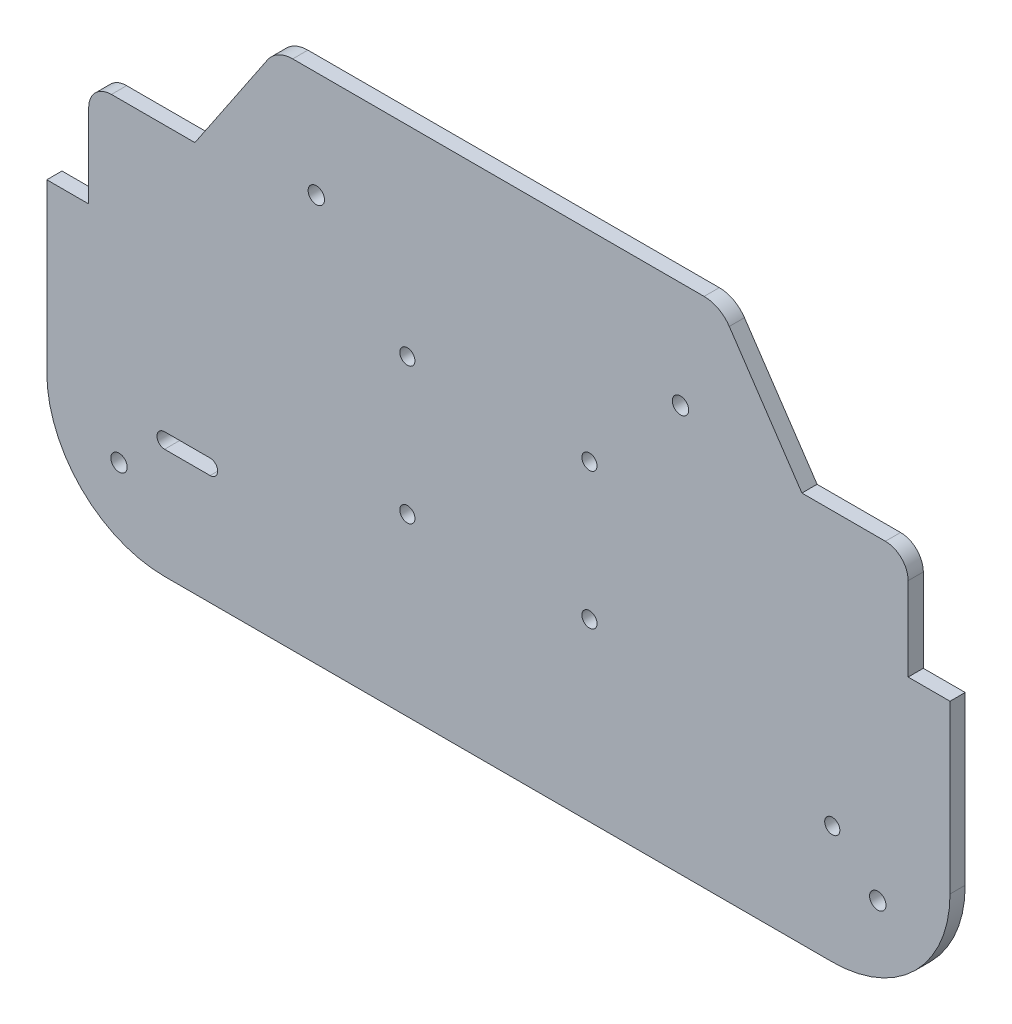
SolidWorks part; units mm, degrees
material "S-Glass Fiber"
ref_plane "Front Plane" through (0, 0, 0) normal (0, 0, 1) x (1, 0, 0)
ref_plane "Top Plane" through (0, 0, 0) normal (0, 1, 0) x (1, 0, 0)
ref_plane "Right Plane" through (0, 0, 0) normal (1, 0, 0) x (0, 0, -1)
ref_plane "Plane1" through (0, 0, -196.85) normal (0, 0, 1) x (1, 0, 0)
sketch "Sketch1" plane through (0, 0, -196.85) normal (0, 0, 1) x (1, 0, 0)
  line L0 (46.4188, -88.9) -> (21.7892, -88.9)
  line L1 (18.1971, -80.2279) -> (61.1779, -37.2471)
  line L2 (69.85, -40.8392) -> (69.85, -65.4688)
  line L3 (-3.5921, -81.3625) -> (-50.8825, -34.0721)
  line L4 (-47.2904, -25.4) -> (47.2904, -25.4)
  line L5 (50.8825, -34.0721) -> (3.5921, -81.3625)
  line L6 (-94.488, -136.525) -> (-94.488, -171.45)
  line L7 (-69.85, -196.088) -> (69.85, -196.088)
  line L8 (94.488, -171.45) -> (94.488, -136.525)
  line L9 (94.488, -136.525) -> (85.725, -136.525)
  line L10 (85.725, -136.525) -> (85.725, -119.0625)
  line L11 (80.9625, -114.3) -> (63.5, -114.3)
  line L12 (63.5, -114.3) -> (63.5, -111.125)
  line L13 (63.5, -111.125) -> (94.488, -111.125)
  line L14 (94.488, -111.125) -> (94.488, -85.725)
  line L15 (94.488, -85.725) -> (88.9, -85.725)
  line L16 (88.9, -85.725) -> (88.9, -60.325)
  line L17 (88.9, -60.325) -> (94.488, -60.325)
  line L18 (94.488, -60.325) -> (94.488, -25.4)
  line L19 (69.85, -0.762) -> (-69.85, -0.762)
  line L20 (-94.488, -25.4) -> (-94.488, -60.325)
  line L21 (-94.488, -60.325) -> (-88.9, -60.325)
  line L22 (-88.9, -60.325) -> (-88.9, -85.725)
  line L23 (-88.9, -85.725) -> (-94.488, -85.725)
  line L24 (-94.488, -85.725) -> (-94.488, -111.125)
  line L25 (-94.488, -111.125) -> (-63.5, -111.125)
  line L26 (-63.5, -111.125) -> (-63.5, -114.3)
  line L27 (-63.5, -114.3) -> (-80.9625, -114.3)
  line L28 (-85.725, -119.0625) -> (-85.725, -136.525)
  line L29 (-85.725, -136.525) -> (-94.488, -136.525)
  line L30 (-69.85, -65.4688) -> (-69.85, -40.8392)
  line L31 (-61.1779, -37.2471) -> (-18.1971, -80.2279)
  line L32 (-21.7892, -88.9) -> (-46.4188, -88.9)
  line L33 (0, 0) -> (0, -50000) construction
  line L34 (-67.0602, -72.204) -> (-53.154, -86.1102)
  line L35 (-19.05, -130.831) -> (19.05, -130.831) construction
  line L36 (-19.05, -130.831) -> (-19.05, -159.406) construction
  line L37 (-19.05, -159.406) -> (19.05, -159.406) construction
  line L38 (19.05, -130.831) -> (19.05, -159.406) construction
  line L39 (-61.1779, -139.7) -> (73.825, -139.7) construction
  line L40 (-61.1779, -139.7) -> (-61.1779, -25.8853) construction
  line L41 (-61.1779, -25.8853) -> (73.825, -25.8853) construction
  line L42 (73.825, -139.7) -> (73.825, -25.8853) construction
  line L43 (67.0602, -72.204) -> (53.154, -86.1102)
  line L44 (88.9, -149.225) -> (88.9, -168.275)
  line L45 (-89.6937, -149.225) -> (-88.9, -149.225)
  line L46 (-89.6937, -149.225) -> (-89.6937, -168.275)
  line L47 (-89.6937, -168.275) -> (-88.9, -168.275)
  line L48 (-88.9, -149.225) -> (-88.9, -168.275)
  line L49 (89.6937, -168.275) -> (88.9, -168.275)
  line L50 (89.6938, -149.225) -> (89.6937, -168.275)
  line L51 (89.6938, -149.225) -> (88.9, -149.225)
  line L52 (-50.8, -196.088) -> (-50.8, -192.913)
  line L53 (-50.8, -192.913) -> (-25.4, -192.913)
  line L54 (-25.4, -192.913) -> (-25.4, -196.088)
  line L55 (-69.85, -169.8625) -> (-60.325, -169.8625)
  line L56 (-69.85, -173.0375) -> (-60.325, -173.0375)
  line L57 (50.8, -196.088) -> (50.8, -192.913)
  line L58 (25.4, -192.913) -> (25.4, -196.088)
  line L59 (50.8, -192.913) -> (25.4, -192.913)
  line L60 (-63.5, -111.125) -> (63.5, -111.125) construction
  line L61 (-63.5, -114.3) -> (-46.4188, -88.9)
  line L62 (63.5, -114.3) -> (46.4188, -88.9)
  line L63 (-21.7892, -88.9) -> (21.7892, -88.9)
  circle A0 centre (-19.05, -12.7) radius 1.5875
  circle A1 centre (19.05, -12.7) radius 1.5875
  circle A2 centre (-69.85, -25.4) radius 1.5875
  circle A3 centre (69.85, -25.4) radius 1.5875
  circle A4 centre (-69.85, -171.45) radius 1.5875
  circle A5 centre (69.85, -171.45) radius 1.5875
  arc A6 (69.85, -65.4688) -> (67.0602, -72.204) centre (60.325, -65.4688) cw
  arc A7 (21.7892, -88.9) -> (18.1971, -80.2279) centre (21.7892, -83.82) cw
  arc A8 (61.1779, -37.2471) -> (69.85, -40.8392) centre (64.77, -40.8392) cw
  circle A9 centre (-83.82, -84.8367) radius 1.5875
  arc A10 (3.5921, -81.3625) -> (-3.5921, -81.3625) centre (0, -77.7704) cw
  arc A11 (-50.8825, -34.0721) -> (-47.2904, -25.4) centre (-47.2904, -30.48) cw
  arc A12 (47.2904, -25.4) -> (50.8825, -34.0721) centre (47.2904, -30.48) cw
  arc A13 (-94.488, -171.45) -> (-69.85, -196.088) centre (-69.85, -171.45) ccw
  arc A14 (69.85, -196.088) -> (94.488, -171.45) centre (69.85, -171.45) ccw
  arc A15 (94.488, -25.4) -> (69.85, -0.762) centre (69.85, -25.4) ccw
  arc A16 (-69.85, -0.762) -> (-94.488, -25.4) centre (-69.85, -25.4) ccw
  arc A17 (-69.85, -40.8392) -> (-61.1779, -37.2471) centre (-64.77, -40.8392) cw
  arc A18 (-18.1971, -80.2279) -> (-21.7892, -88.9) centre (-21.7892, -83.82) cw
  arc A19 (46.4188, -88.9) -> (53.154, -86.1102) centre (46.4188, -79.375) ccw
  arc A20 (85.725, -119.0625) -> (80.9625, -114.3) centre (80.9625, -119.0625) ccw
  arc A21 (-80.9625, -114.3) -> (-85.725, -119.0625) centre (-80.9625, -119.0625) ccw
  circle A22 centre (-19.05, -130.831) radius 1.5875
  circle A23 centre (19.05, -130.831) radius 1.5875
  circle A24 centre (19.05, -159.406) radius 1.5875
  circle A25 centre (-19.05, -159.406) radius 1.5875
  arc A26 (-46.4188, -88.9) -> (-53.154, -86.1102) centre (-46.4188, -79.375) cw
  arc A27 (-69.85, -65.4688) -> (-67.0602, -72.204) centre (-60.325, -65.4688) ccw
  circle A28 centre (-60.325, -171.45) radius 1.5875
  circle A29 centre (-38.1, -111.125) radius 1.7145
  circle A30 centre (38.1, -111.125) radius 1.7145
  circle A31 centre (-79.375, -180.213) radius 1.7145
  circle A32 centre (79.375, -180.213) radius 1.7145
  point P84 (0, -130.831)
  point P95 (-69.85, -69.4142)
  dimension "D1" = 4.7625
  dimension "D4" = 3.175
  dimension "D7" = 3.175
  dimension "D11" = 9.525
  dimension "D20" = 3.429
  dimension "D21" = 76.2
  dimension "D22" = 158.75
  dimension "D2" = 38.1
  dimension "D3" = 28.575
  dimension "D5" = 56.388
  dimension "D6" = 19.706
  dimension "D8" = 9.525
  dimension "D9" = 9.525
  dimension "D10" = 28.575
  dimension "D12" = 0.7937
  dimension "D13" = 19.05
  dimension "D14" = 12.7
  dimension "D15" = 3.175
  dimension "D16" = 3.175
  dimension "D17" = 25.4
  dimension "D18" = 25.4
  dimension "D19" = 9.525
  dimension "D23" = 15.875
extrude "Boss-Extrude1" add sketch "Sketch1" against normal blind 3.175 contours L27 A21 L28 L29 L6 A13 L7 L52 L53 L54 L58 L59 L57 A14 L8 L9 L10 A20 L11 L62 L0 L63 L32 L61 A30 A29 A28 L56 A4 L55 A25 A24 A23 A22 L51 L50 L49 L44 L45 L48 | L54 L53 L52 L7 | L57 L59 L58 L7 | L48 L45 L46 L47 | L50 L51 L44 L49
fillet "Fillet1" radius 6.35 2 edges at (46.4188, -88.9, -198.4375) (-46.4188, -88.9, -198.4375)
